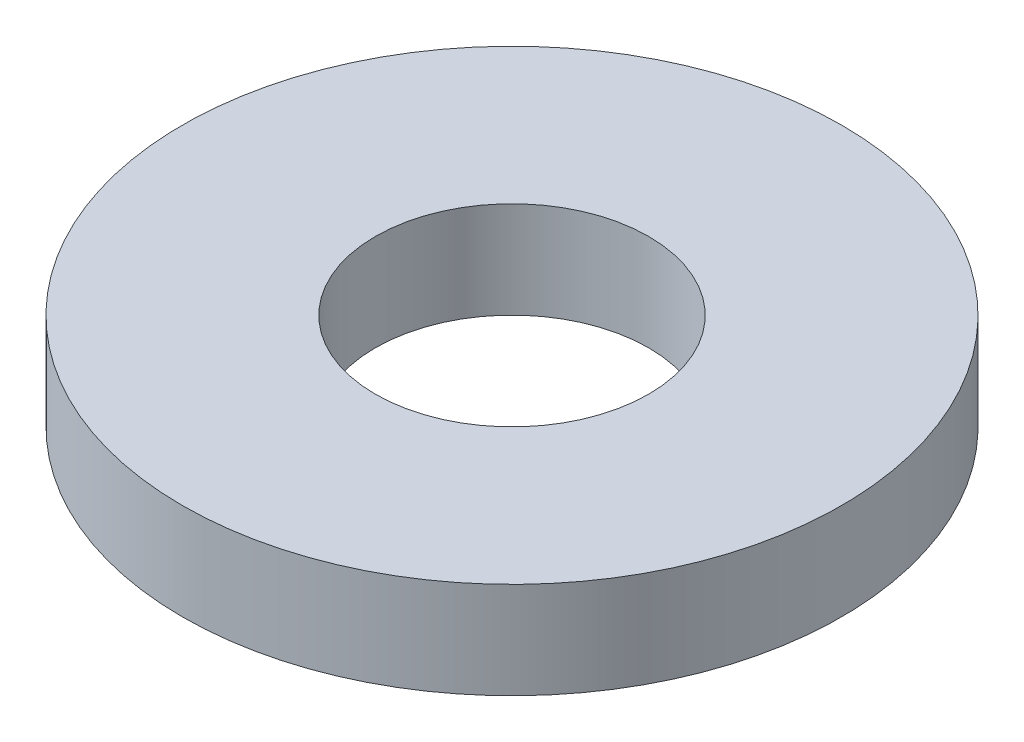
SolidWorks part; units mm, degrees
material "Nylon 6/10"
ref_plane "Front Plane" through (0, 0, 0) normal (0, 0, 1) x (1, 0, 0)
ref_plane "Top Plane" through (0, 0, 0) normal (0, 1, 0) x (1, 0, 0)
ref_plane "Right Plane" through (0, 0, 0) normal (1, 0, 0) x (0, 0, -1)
sketch "Sketch1" plane through (0, 0, 0) normal (0, 1, 0) x (1, 0, 0)
  circle A0 centre (0, 0) radius 2.159
  circle A1 centre (0, 0) radius 5.207
  dimension "D1" = 4.318
  dimension "D2" = 10.414
extrude "Boss-Extrude1" add sketch "Sketch1" along normal blind 1.524
